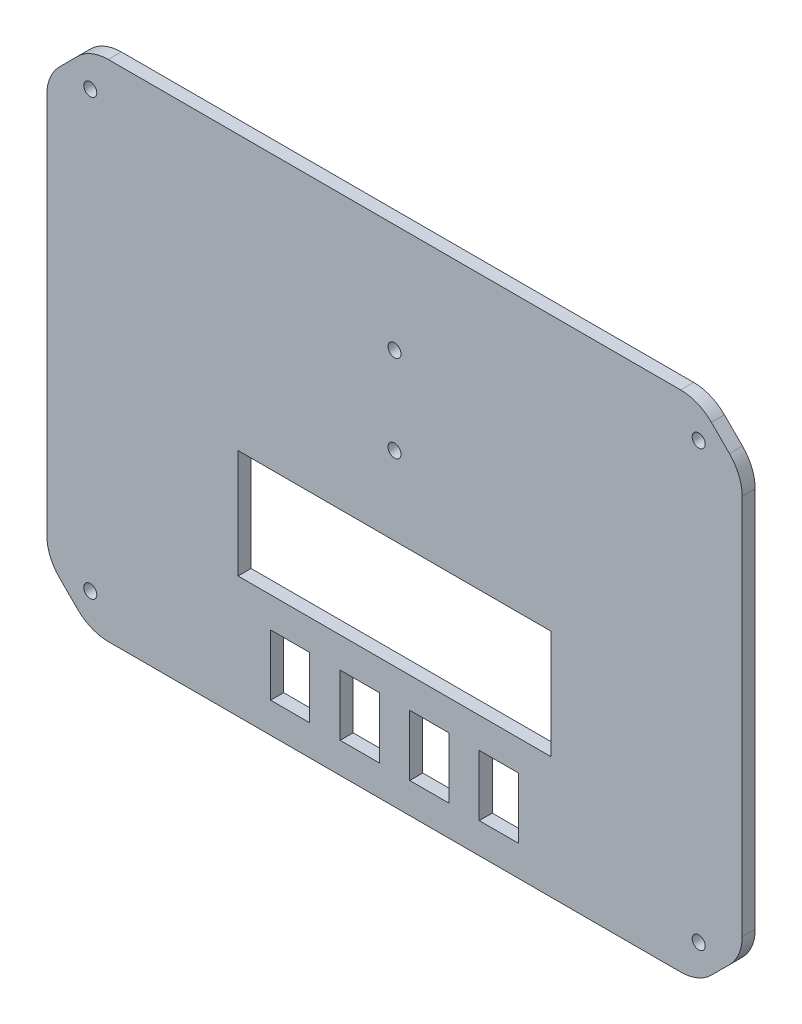
SolidWorks part; units mm, degrees
ref_plane "Front Plane" through (0, 0, 0) normal (0, 0, 1) x (1, 0, 0)
ref_plane "Top Plane" through (0, 0, 0) normal (0, 1, 0) x (1, 0, 0)
ref_plane "Right Plane" through (0, 0, 0) normal (1, 0, 0) x (0, 0, -1)
sketch "Sketch1" plane through (0, 0, 0) normal (0, 0, 1) x (1, 0, 0)
  line L0 (0, 0) -> (0, 116) construction
  line L1 (80, 116) -> (-80, 116)
  line L2 (-80, 116) -> (-80, 10)
  line L3 (-80, 10) -> (-70, 0)
  line L4 (-70, 0) -> (70, 0)
  line L5 (80, 10) -> (70, 0)
  line L6 (80, 116) -> (80, 10)
  dimension "D1" = 80
  dimension "D2" = 106
  dimension "D3" = 116
  dimension "D4" = 135
extrude "Boss-Extrude1" add sketch "Sketch1" along normal blind 3
sketch "Sketch3" plane through (0, 0, 0) normal (0, 0, -1) x (-1, 0, 0)
  line L0 (-80, 106) -> (-70, 116)
  line L1 (-80, 10) -> (-80, 116) construction
  line L2 (-80, 116) -> (80, 116) construction
  dimension "D1" = 135
  dimension "D2" = 10
extrude "Cut-Extrude1" cut sketch "Sketch3" against normal blind 3 and the other way through all
sketch "Sketch4" plane through (0, 0, 0) normal (0, 0, -1) x (-1, 0, 0)
  line L0 (70, 116) -> (80, 106)
  line L1 (-70, 116) -> (80, 116) construction
  line L2 (80, 116) -> (80, 10) construction
  dimension "D1" = 135
  dimension "D2" = 10
extrude "Cut-Extrude2" cut sketch "Sketch4" against normal blind 3 and the other way through all
sketch "Sketch5" plane through (0, 0, 0) normal (0, 0, -1) x (-1, 0, 0)
  line L0 (-80, 10) -> (-80, 106) construction
  line L1 (-36, 53) -> (36, 53)
  line L2 (-36, 53) -> (-36, 28)
  line L3 (-36, 28) -> (36, 28)
  line L4 (36, 53) -> (36, 28)
  line L5 (-70, 116) -> (70, 116) construction
  line L6 (70, 0) -> (-70, 0) construction
  line L7 (80, 106) -> (80, 10) construction
  line L9 (-28.5, 21) -> (-19.5, 21)
  line L10 (-28.5, 21) -> (-28.5, 7)
  line L11 (-28.5, 7) -> (-19.5, 7)
  line L12 (-19.5, 21) -> (-19.5, 7)
  line L13 (-12.5, 21) -> (-3.5, 21)
  line L14 (-12.5, 21) -> (-12.5, 7)
  line L15 (-12.5, 7) -> (-3.5, 7)
  line L16 (-3.5, 21) -> (-3.5, 7)
  line L17 (3.5, 21) -> (12.5, 21)
  line L18 (3.5, 21) -> (3.5, 7)
  line L19 (3.5, 7) -> (12.5, 7)
  line L20 (12.5, 21) -> (12.5, 7)
  line L21 (19.5, 21) -> (28.5, 21)
  line L22 (19.5, 21) -> (19.5, 7)
  line L23 (19.5, 7) -> (28.5, 7)
  line L24 (28.5, 21) -> (28.5, 7)
  circle A0 centre (0, 91) radius 1.5
  circle A1 centre (0, 71) radius 1.5
  circle A2 centre (-70, 8) radius 1.5
  circle A3 centre (70, 8) radius 1.5
  circle A4 centre (70, 108) radius 1.5
  circle A5 centre (-70, 108) radius 1.5
  point P40 (0, 0)
  point P41 (0, 0)
  point P42 (0, 0)
  point P43 (0, 0)
  point P44 (0, 0)
  point P45 (0, 0)
  dimension "D6" = 3
  dimension "D28" = 3
  dimension "D1" = 72
  dimension "D2" = 25
  dimension "D3" = 20
  dimension "D4" = 25
  dimension "D5" = 70
  dimension "D7" = 28
  dimension "D8" = 44
  dimension "D9" = 14
  dimension "D10" = 9
  dimension "D11" = 14
  dimension "D12" = 9
  dimension "D13" = 14
  dimension "D14" = 9
  dimension "D15" = 14
  dimension "D16" = 9
  dimension "D17" = 7
  dimension "D18" = 7
  dimension "D19" = 7
  dimension "D20" = 41.5
  dimension "D21" = 7
  dimension "D22" = 7
  dimension "D23" = 7
  dimension "D24" = 7
  dimension "D25" = 10
  dimension "D26" = 8
  dimension "D27" = 10
  dimension "D29" = 8
extrude "Cut-Extrude3" cut sketch "Sketch5" against normal through all
fillet "Fillet1" radius 10 8 edges at (80, 106, 1.5) (70, 116, 1.5) (-70, 116, 1.5) (-80, 106, 1.5) (-80, 10, 1.5) (-70, 0, 1.5) (70, 0, 1.5) (80, 10, 1.5)
